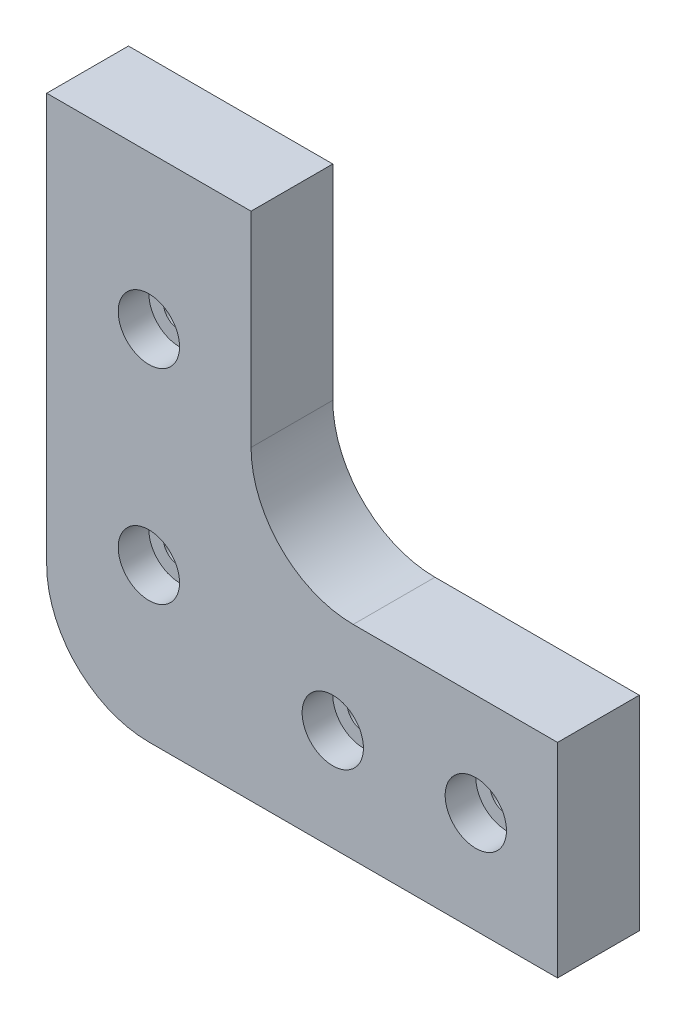
SolidWorks part; units mm, degrees
ref_plane "前视基准面" through (0, 0, 0) normal (0, 0, 1) x (1, 0, 0)
ref_plane "上视基准面" through (0, 0, 0) normal (0, 1, 0) x (1, 0, 0)
ref_plane "右视基准面" through (0, 0, 0) normal (1, 0, 0) x (0, 0, -1)
other "Configuration Table"
sketch "草图1" plane through (0, 0, 0) normal (0, 0, 1) x (1, 0, 0)
  line L0 (-10, 77.5) -> (-10, -160) construction
  line L1 (-10, -110) -> (10, -110)
  line L2 (-10, -110) -> (-10, -160)
  line L4 (10, -110) -> (10, -140.0288)
  line L5 (-10, -160) -> (40, -160)
  line L7 (10, -140.0288) -> (40, -140.0288)
  line L8 (40, -160) -> (40, -140.0288)
  line L9 (184.3942, -160) -> (10.0042, -160) construction
  line L10 (10, -130.0288) -> (10, 47.5288) construction
  line L11 (174.3942, -140.0288) -> (20, -140.0288) construction
  circle A0 centre (0, -125) radius 1.6
  circle A1 centre (0, -145) radius 1.6
  circle A2 centre (18, -150.0144) radius 1.6
  circle A3 centre (32, -150.0144) radius 1.6
  point P22 (0, -110)
  point P23 (40, -150.0144)
  dimension "D2" = 3.2
  dimension "D4" = 15
  dimension "D1" = 50
  dimension "D3" = 15
  dimension "D5" = 8
  dimension "D6" = 8
extrude "凸台-拉伸1" add sketch "草图1" along normal blind 8
sketch "草图2" plane through (0, 0, 8) normal (0, 0, 1) x (1, 0, 0)
  circle A0 centre (32, -150.0144) radius 3
  circle A1 centre (32, -150.0144) radius 1.6
  circle A2 centre (32, -150.0144) radius 1.6 construction
  circle A3 centre (18, -150.0144) radius 1.6
  circle A4 centre (18, -150.0144) radius 1.6 construction
  circle A5 centre (0, -145) radius 1.6
  circle A6 centre (0, -145) radius 1.6 construction
  circle A7 centre (0, -125) radius 1.6
  circle A8 centre (0, -125) radius 1.6 construction
  circle A9 centre (18, -150.0144) radius 3
  circle A10 centre (0, -145) radius 3
  circle A11 centre (0, -125) radius 3
  dimension "D1" = 6
  dimension "D2" = 0
  dimension "D3" = 0
  dimension "D4" = 0
  dimension "D5" = 0
extrude "切除-拉伸1" cut sketch "草图2" against normal blind 3
fillet "圆角1" radius 10 2 edges at (10, -140.0288, 4) (-10, -160, 4)
